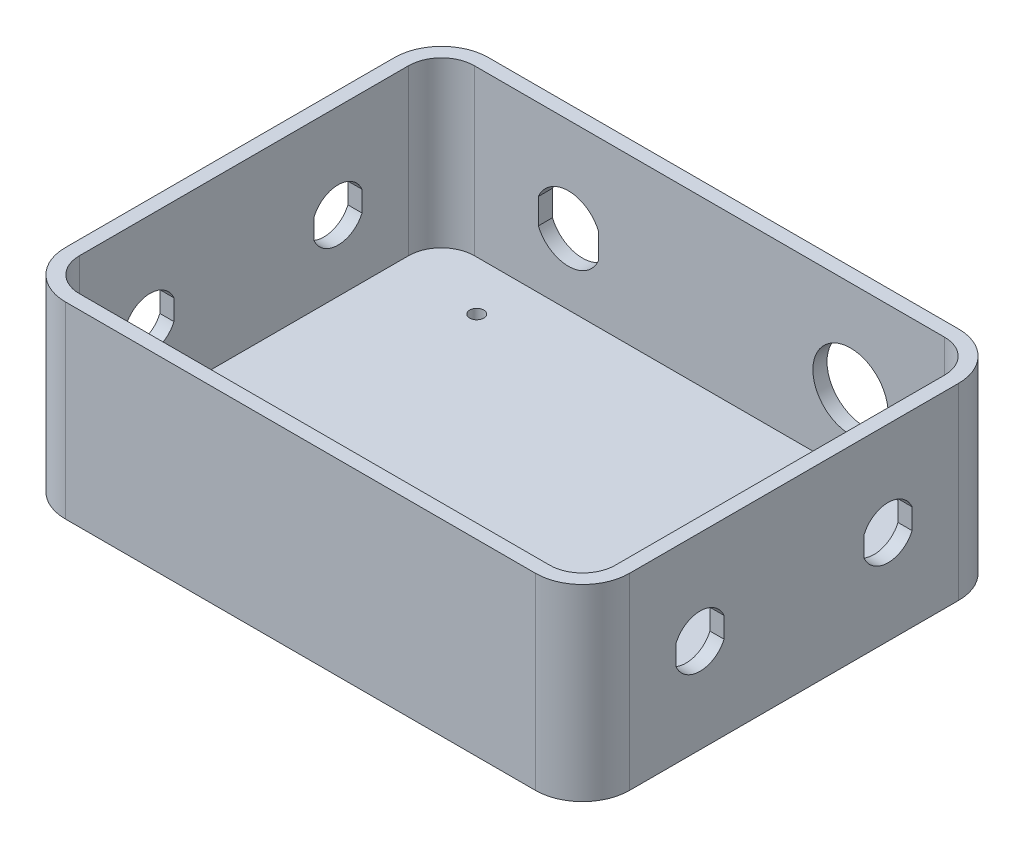
SolidWorks part; units mm, degrees
ref_plane "Front Plane" through (0, 0, 0) normal (0, 0, 1) x (1, 0, 0)
ref_plane "Top Plane" through (0, 0, 0) normal (0, 1, 0) x (1, 0, 0)
ref_plane "Right Plane" through (0, 0, 0) normal (1, 0, 0) x (0, 0, -1)
sketch "Sketch1" plane through (0, 0, 0) normal (0, 1, 0) x (1, 0, 0)
  line L1 (10, 0) -> (110, 0)
  line L2 (0, 10) -> (0, 80)
  line L3 (10, 90) -> (110, 90)
  line L4 (120, 10) -> (120, 80)
  arc A0 (10, 0) -> (0, 10) centre (10, 10) cw
  arc A1 (110, 0) -> (120, 10) centre (110, 10) ccw
  arc A2 (110, 90) -> (120, 80) centre (110, 80) cw
  arc A3 (0, 80) -> (10, 90) centre (10, 80) cw
  point P7 (0, 0)
  point P10 (120, 0)
  point P13 (120, 90)
  dimension "D3" = 10
  dimension "D1" = 120
  dimension "D2" = 90
extrude "Boss-Extrude1" add sketch "Sketch1" along normal blind 5
sketch "Sketch5" plane through (0, 5, 0) normal (0, 1, 0) x (1, 0, 0)
  line L0 (0, 45) -> (120, 45) construction
  line L1 (0, 80) -> (0, 10) construction
  line L2 (120, 10) -> (120, 80) construction
  line L3 (21, 13.5) -> (21, 76.5) construction
  line L4 (15, 7.5) -> (105, 7.5) construction
  line L5 (15, 7.5) -> (15, 82.5) construction
  line L6 (15, 82.5) -> (105, 82.5) construction
  line L7 (105, 7.5) -> (105, 82.5) construction
  line L8 (15, 7.5) -> (105, 82.5) construction
  line L9 (15, 82.5) -> (105, 7.5) construction
  line L10 (21, 13.5) -> (99, 13.5) construction
  circle A1 centre (21, 76.5) radius 1.5
  circle A2 centre (21, 13.5) radius 1.5
  circle A3 centre (99, 13.5) radius 1.5
  circle A4 centre (99, 76.5) radius 1.5
  point P6 (60, 45)
  point P11 (21, 76.5)
  point P13 (21, 13.5)
  point P15 (99, 13.5)
  point P17 (99, 76.5)
  point P19 (21, 45)
  point P20 (60, 13.5)
  dimension "D3" = 3
  dimension "D1" = 75
  dimension "D2" = 90
  dimension "D4" = 63
  dimension "D5" = 78
hole_wizard "Ø3.0 (3) Diameter Hole1" positions "Sketch5" profile "Sketch6" hole size "Ø3.0" standard "ISO"
sketch "Sketch6" plane through (99, 5, -76.5) normal (1, 0, 0) x (0, 0, 1)
  line L0 (0, 0) -> (0, 3.9013)
  line L1 (0, 3.9013) -> (1.5, 3)
  line L2 (1.5, 3) -> (1.5, 0)
  line L5 (1.5, 0) -> (0, 0)
  line L10 (0, 3.9013) -> (-1.5, 3) construction
  line L11 (0, -6.35) -> (0, 107.95) construction
  dimension "Hole Dia." = 3
  dimension "Hole Depth" = 3
  dimension "Drill Angle" = 118
sketch "Sketch7" plane through (0, 5, 0) normal (0, 1, 0) x (1, 0, 0)
  line L0 (3, 80) -> (3, 10)
  line L1 (10, 3) -> (110, 3)
  line L2 (117, 10) -> (117, 80)
  line L3 (110, 87) -> (10, 87)
  line L4 (10, 0) -> (110, 0)
  line L5 (120, 10) -> (120, 80)
  line L6 (110, 90) -> (10, 90)
  line L7 (0, 80) -> (0, 10)
  line L8 (10, 0) -> (110, 0)
  line L9 (120, 10) -> (120, 80)
  line L10 (110, 90) -> (10, 90)
  line L11 (0, 80) -> (0, 10)
  arc A0 (3, 10) -> (10, 3) centre (10, 10) ccw
  arc A1 (110, 3) -> (117, 10) centre (110, 10) ccw
  arc A2 (117, 80) -> (110, 87) centre (110, 80) ccw
  arc A3 (10, 87) -> (3, 80) centre (10, 80) ccw
  arc A4 (0, 10) -> (10, 0) centre (10, 10) ccw
  arc A5 (110, 0) -> (120, 10) centre (110, 10) ccw
  arc A6 (120, 80) -> (110, 90) centre (110, 80) ccw
  arc A7 (10, 90) -> (0, 80) centre (10, 80) ccw
  arc A8 (0, 10) -> (10, 0) centre (10, 10) ccw
  arc A9 (110, 0) -> (120, 10) centre (110, 10) ccw
  arc A10 (120, 80) -> (110, 90) centre (110, 80) ccw
  arc A11 (10, 90) -> (0, 80) centre (10, 80) ccw
  dimension "D1" = 0
  dimension "D2" = 3
extrude "Boss-Extrude2" add sketch "Sketch7" along normal blind 35
sketch "Sketch8" plane through (0, 0, 0) normal (-1, 0, 0) x (0, 0, 1)
  line L0 (-59.9, 22.1892) -> (-59.9, 17.8108)
  line L1 (-70.1, 22.1892) -> (-70.1, 17.8108)
  line L2 (-70.1, 21.3574) -> (-59.9, 21.3574) construction
  line L3 (-80, 40) -> (-10, 40) construction
  line L4 (-80, 40) -> (-80, 0) construction
  line L5 (-45, 0) -> (-45, 40) construction
  line L6 (-80, 0) -> (-10, 0) construction
  line L7 (-19.9, 22.1892) -> (-19.9, 17.8108)
  line L8 (-30.1, 22.1892) -> (-30.1, 17.8108)
  arc A0 (-59.9, 22.1892) -> (-70.1, 22.1892) centre (-65, 20) ccw
  arc A2 (-70.1, 17.8108) -> (-59.9, 17.8108) centre (-65, 20) ccw
  arc A3 (-30.1, 22.1892) -> (-19.9, 22.1892) centre (-25, 20) cw
  arc A4 (-19.9, 17.8108) -> (-30.1, 17.8108) centre (-25, 20) cw
  point P6 (-65, 21.3574)
  dimension "D1" = 11.1
  dimension "D2" = 10.2
  dimension "D3" = 20
  dimension "D4" = 15
extrude "Cut-Extrude1" cut sketch "Sketch8" against normal blind 149
sketch "Sketch9" plane through (0, 0, -90) normal (0, 0, -1) x (-1, 0, 0)
  line L0 (-36.4, 22.7097) -> (-36.4, 17.2903)
  line L1 (-23.6, 22.7097) -> (-23.6, 17.2903)
  line L2 (-36.4, 20) -> (-23.6, 20) construction
  line L3 (-110, 40) -> (-10, 40) construction
  line L4 (-10, 40) -> (-10, 0) construction
  arc A0 (-36.4, 17.2903) -> (-23.6, 17.2903) centre (-30, 20) ccw
  arc A1 (-23.6, 22.7097) -> (-36.4, 22.7097) centre (-30, 20) ccw
  point P8 (0, 0)
  point P9 (0, 0)
  dimension "D1" = 13.9
  dimension "D2" = 12.8
  dimension "D3" = 20
  dimension "D4" = 20
extrude "Cut-Extrude2" cut sketch "Sketch9" against normal blind 35
sketch "Sketch10" plane through (0, 0, -90) normal (0, 0, -1) x (-1, 0, 0)
  line L0 (-110, 40) -> (-10, 40) construction
  line L1 (-110, 40) -> (-110, 0) construction
  circle A0 centre (-90, 20) radius 8
  dimension "D1" = 16
  dimension "D2" = 20
  dimension "D3" = 20
extrude "Cut-Extrude3" cut sketch "Sketch10" against normal blind 35
